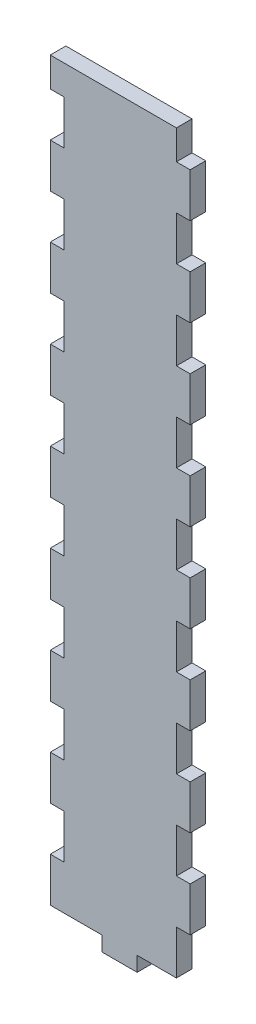
SolidWorks part; units mm, degrees
ref_plane "Front Plane" through (0, 0, 0) normal (0, 0, 1) x (1, 0, 0)
ref_plane "Top Plane" through (0, 0, 0) normal (0, 1, 0) x (1, 0, 0)
ref_plane "Right Plane" through (0, 0, 0) normal (1, 0, 0) x (0, 0, -1)
sketch "Sketch1" plane through (0, 0, 0) normal (0, 0, 1) x (1, 0, 0)
  line L0 (-28.5, 0) -> (-17.915, 0)
  line L1 (0, 0) -> (-10.795, 0)
  line L2 (0, 0) -> (0, 150)
  line L3 (0, 150) -> (-28.5, 150)
  line L4 (-28.5, 0) -> (-28.5, 150)
  line L5 (-17.915, 0) -> (-28.5, 0)
  line L7 (-17.915, 0) -> (-17.915, -3)
  line L8 (-17.915, -3) -> (-10.795, -3)
  line L9 (-10.795, 0) -> (-10.795, -3)
  dimension "D1" = 150
  dimension "D2" = 28.5
  dimension "D3" = 10.585
  dimension "D4" = 3
  dimension "D5" = 7.12
extrude "Boss-Extrude1" add sketch "Sketch1" along normal blind 3.18 contours L9 L1 L2 L3 L4 L0 L7 L8
sketch "Sketch2" plane through (0, 0, 3.18) normal (0, 0, 1) x (1, 0, 0)
  line L0 (-28.5, 9) -> (-28.5, 0) construction
  line L1 (-28.5, 0) -> (-28.5, 150) construction
  line L2 (-28.5, 9) -> (-25.7, 9)
  line L3 (-25.7, 9) -> (-25.7, 18)
  line L4 (-25.7, 18) -> (-28.5, 18)
  line L5 (-28.5, 18) -> (-28.5, 27) construction
  line L6 (-28.5, 27) -> (-25.7, 27)
  line L7 (-25.7, 27) -> (-25.7, 36)
  line L8 (-25.7, 36) -> (-28.5, 36)
  line L9 (-28.5, 36) -> (-28.5, 45) construction
  line L10 (-28.5, 45) -> (-25.7, 45)
  line L11 (-25.7, 45) -> (-25.7, 54)
  line L12 (-25.7, 54) -> (-28.5, 54)
  line L13 (-28.5, 54) -> (-28.5, 63) construction
  line L14 (-28.5, 63) -> (-25.7, 63)
  line L15 (-25.7, 63) -> (-25.7, 72)
  line L16 (-25.7, 72) -> (-28.5, 72)
  line L17 (-28.5, 72) -> (-28.5, 81) construction
  line L18 (-28.5, 81) -> (-25.7, 81)
  line L19 (-25.7, 81) -> (-25.7, 90)
  line L20 (-25.7, 90) -> (-28.5, 90)
  line L21 (-28.5, 90) -> (-28.5, 99) construction
  line L22 (-28.5, 99) -> (-25.7, 99)
  line L23 (-25.7, 99) -> (-25.7, 108)
  line L24 (-25.7, 108) -> (-28.5, 108)
  line L25 (-28.5, 108.4047) -> (-28.5, 108) construction
  line L26 (-28.5, 108) -> (-28.5, 117) construction
  line L27 (-28.5, 117) -> (-25.7, 117)
  line L28 (-25.7, 117) -> (-25.7, 126)
  line L29 (-25.7, 126) -> (-28.5, 126)
  line L30 (-28.5, 126) -> (-28.5, 135) construction
  line L31 (-28.5, 135) -> (-25.7, 135)
  line L32 (-25.7, 135) -> (-25.7, 144)
  line L33 (-25.7, 144) -> (-28.5, 144)
  line L34 (0, 0) -> (-2.8, 0)
  line L35 (0, 0) -> (-10.795, 0) construction
  line L36 (-2.8, 0) -> (-2.8, 9)
  line L37 (-2.8, 9) -> (0, 9)
  line L38 (0, 0) -> (0, 150) construction
  line L39 (0, 9) -> (0, 18) construction
  line L40 (0, 18) -> (-2.8, 18)
  line L41 (-2.8, 18) -> (-2.8, 27)
  line L42 (-2.8, 27) -> (0, 27)
  line L43 (0, 27) -> (0, 36) construction
  line L44 (0, 36) -> (-2.8, 36)
  line L45 (-2.8, 36) -> (-2.8, 45)
  line L46 (-2.8, 45) -> (0, 45)
  line L47 (0, 45) -> (0, 54) construction
  line L48 (0, 54) -> (-2.8, 54)
  line L49 (-2.8, 54) -> (-2.8, 63)
  line L50 (-2.8, 63) -> (0, 63)
  line L51 (0, 63) -> (0, 54)
  line L52 (0, 45) -> (0, 36)
  line L53 (0, 27) -> (0, 18)
  line L54 (0, 9) -> (0, 0)
  line L55 (0, 63) -> (0, 72) construction
  line L56 (0, 72) -> (-2.8, 72)
  line L57 (-2.8, 72) -> (-2.8, 81)
  line L58 (-2.8, 81) -> (0, 81)
  line L59 (0, 81) -> (0, 72)
  line L60 (0, 81) -> (0, 90) construction
  line L61 (0, 90) -> (-2.8, 90)
  line L62 (-2.8, 90) -> (-2.8, 99)
  line L63 (-2.8, 99) -> (0, 99)
  line L64 (0, 99) -> (0, 90)
  line L65 (0, 99) -> (0, 108) construction
  line L66 (0, 108) -> (-2.8, 108)
  line L67 (-2.8, 108) -> (-2.8, 117)
  line L68 (-2.8, 117) -> (0, 117)
  line L69 (0, 117) -> (0, 108)
  line L70 (0, 117) -> (0, 126) construction
  line L71 (0, 126) -> (-2.8, 126)
  line L72 (-2.8, 126) -> (-2.8, 135)
  line L73 (-2.8, 135) -> (0, 135)
  line L74 (0, 135) -> (0, 126)
  line L75 (0, 135) -> (0, 144) construction
  line L76 (0, 144) -> (-2.8, 144)
  line L77 (-2.8, 144) -> (-2.8, 150)
  line L78 (0, 150) -> (-28.5, 150) construction
  line L79 (-2.8, 150) -> (0, 150)
  line L80 (0, 150) -> (0, 144)
  line L81 (-28.5, 144) -> (-28.5, 135)
  line L82 (-28.5, 126) -> (-28.5, 117)
  line L83 (-28.5, 108) -> (-28.5, 99)
  line L84 (-28.5, 90) -> (-28.5, 81)
  line L85 (-28.5, 72) -> (-28.5, 63)
  line L86 (-28.5, 54) -> (-28.5, 45)
  line L87 (-28.5, 36) -> (-28.5, 27)
  line L88 (-28.5, 18) -> (-28.5, 9)
  dimension "D1" = 9
  dimension "D2" = 9
  dimension "D3" = 2.8
  dimension "D4" = 9
  dimension "D5" = 9
  dimension "D6" = 2.8
  dimension "D7" = 9
  dimension "D8" = 9
  dimension "D9" = 2.8
  dimension "D10" = 9
  dimension "D11" = 9
  dimension "D12" = 2.8
  dimension "D13" = 9
  dimension "D14" = 9
  dimension "D15" = 2.8
  dimension "D16" = 9
  dimension "D17" = 9
  dimension "D18" = 2.8
  dimension "D19" = 9
  dimension "D20" = 9
  dimension "D21" = 2.8
  dimension "D22" = 9
  dimension "D23" = 9
  dimension "D24" = 2.8
  dimension "D25" = 2.8
  dimension "D26" = 9
extrude "Cut-Extrude1" cut sketch "Sketch2" against normal through all
